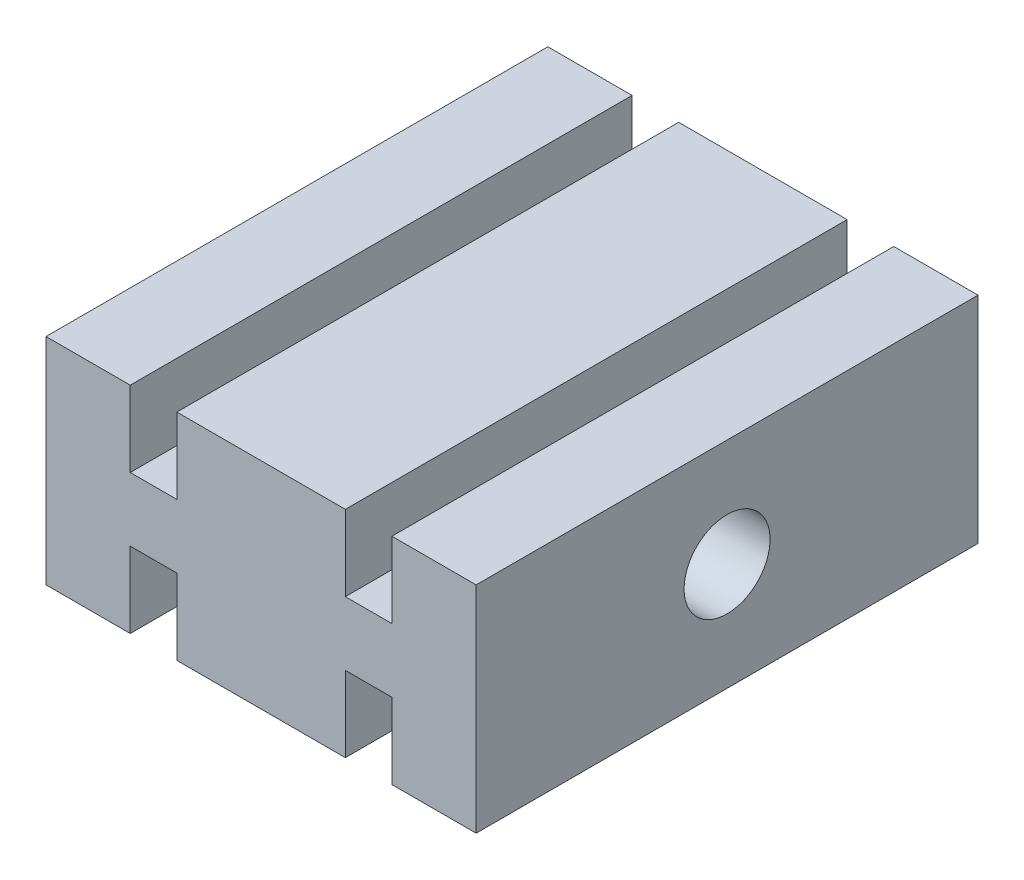
SolidWorks part; units mm, degrees
ref_plane "Front Plane" through (0, 0, 0) normal (0, 0, 1) x (1, 0, 0)
ref_plane "Top Plane" through (0, 0, 0) normal (0, 1, 0) x (1, 0, 0)
ref_plane "Right Plane" through (0, 0, 0) normal (1, 0, 0) x (0, 0, -1)
sketch "Sketch1" plane through (0, 0, 0) normal (0, 0, 1) x (1, 0, 0)
  line L1 (-30, -15) -> (30, -15)
  line L2 (-30, -15) -> (-30, 15)
  line L3 (-30, 15) -> (30, 15)
  line L4 (30, -15) -> (30, 15)
  line L5 (-30, -15) -> (30, 15) construction
  line L6 (-30, 15) -> (30, -15) construction
  point P0 (0, 0)
  dimension "D1" = 60
  dimension "D2" = 30
extrude "Boss-Extrude1" add sketch "Sketch1" along normal mid plane 70
sketch "Sketch3" plane through (0, 0, 0) normal (0, 0, 1) x (1, 0, 0)
  line L0 (30, 15) -> (-30, 15) construction
  line L1 (11.75, 15) -> (18.25, 15)
  line L2 (11.75, 15) -> (11.75, 4.45)
  line L3 (11.75, 4.45) -> (18.25, 4.45)
  line L4 (18.25, 15) -> (18.25, 4.45)
  line L5 (-30, -15) -> (30, -15) construction
  line L6 (-18.25, 15) -> (-11.75, 15)
  line L7 (-18.25, 15) -> (-18.25, 4.45)
  line L8 (-18.25, 4.45) -> (-11.75, 4.45)
  line L9 (-11.75, 15) -> (-11.75, 4.45)
  line L10 (-18.25, -15) -> (-11.75, -15)
  line L11 (-18.25, -15) -> (-18.25, -4.45)
  line L12 (-18.25, -4.45) -> (-11.75, -4.45)
  line L13 (-11.75, -15) -> (-11.75, -4.45)
  line L14 (0, 0) -> (0, 15) construction
  line L15 (11.75, -15) -> (18.25, -15)
  line L16 (11.75, -15) -> (11.75, -4.45)
  line L17 (11.75, -4.45) -> (18.25, -4.45)
  line L18 (18.25, -15) -> (18.25, -4.45)
  line L19 (0, 0) -> (30, 0) construction
  line L20 (30, -15) -> (30, 15) construction
  line L21 (-15, 4.45) -> (15, 4.45) construction
  dimension "D1" = 30
  dimension "D2" = 6.5
  dimension "D3" = 10.55
extrude "Cut-Extrude1" cut sketch "Sketch3" against normal through all both and the other way through all
sketch "Sketch4" plane through (-30, 0, 0) normal (-1, 0, 0) x (0, 0, 1)
  circle A0 centre (0, 0) radius 6
  dimension "D1" = 12
extrude "Cut-Extrude2" cut sketch "Sketch4" against normal through all both and the other way through all
